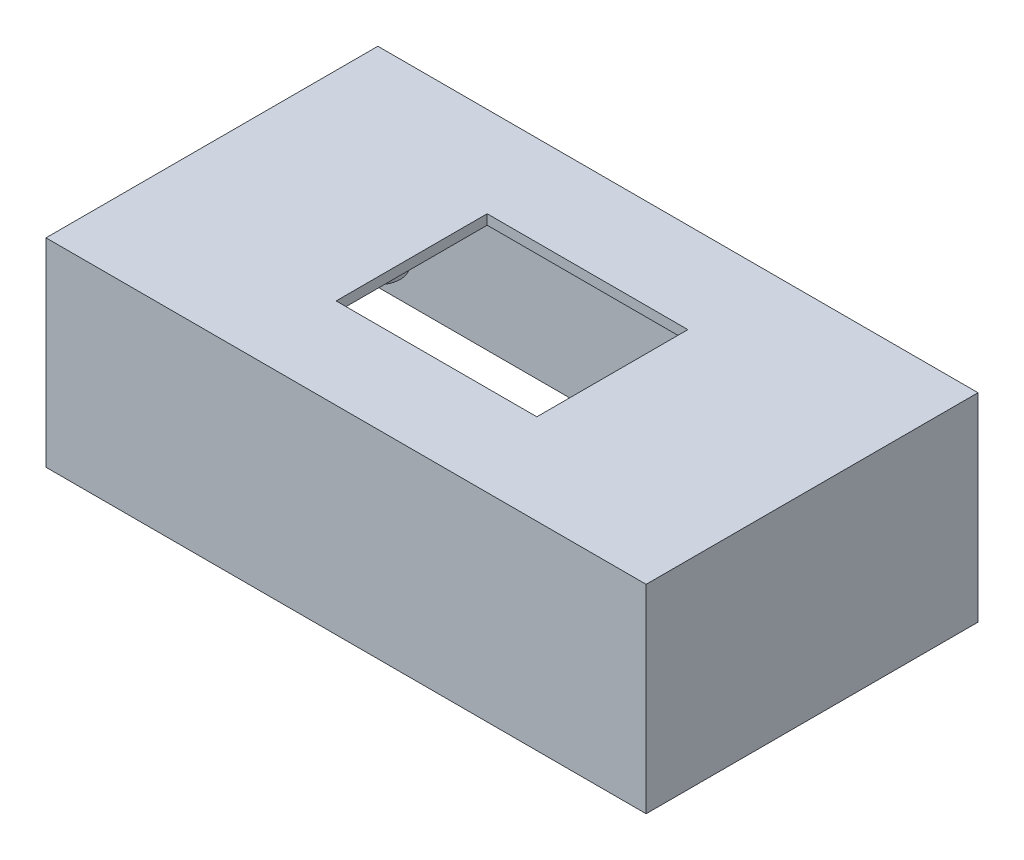
SolidWorks part; units mm, degrees
ref_plane "Front Plane" through (0, 0, 0) normal (0, 0, 1) x (1, 0, 0)
ref_plane "Top Plane" through (0, 0, 0) normal (0, 1, 0) x (1, 0, 0)
ref_plane "Right Plane" through (0, 0, 0) normal (1, 0, 0) x (0, 0, -1)
sketch "Sketch1" plane through (0, 0, 0) normal (0, 1, 0) x (1, 0, 0)
  line L0 (-29.2, 15.7) -> (29.2, 15.7)
  line L1 (-29, -15.5) -> (29, -15.5) construction
  line L2 (-29, -15.5) -> (-29, 15.5) construction
  line L3 (-29, 15.5) -> (29, 15.5) construction
  line L4 (29, -15.5) -> (29, 15.5) construction
  line L5 (-29, -15.5) -> (29, 15.5) construction
  line L6 (-29, 15.5) -> (29, -15.5) construction
  line L7 (29.2, -15.7) -> (29.2, 15.7)
  line L8 (-29.2, -15.7) -> (29.2, -15.7)
  line L9 (-29.2, -15.7) -> (-29.2, 15.7)
  line L10 (-30.2, -16.7) -> (-30.2, 16.7)
  line L11 (-30.2, 16.7) -> (30.2, 16.7)
  line L12 (30.2, -16.7) -> (30.2, 16.7)
  line L13 (-30.2, -16.7) -> (30.2, -16.7)
  point P0 (0, 0)
  dimension "D1" = 58
  dimension "D2" = 31
  dimension "D3" = 0.2
  dimension "D4" = 1
extrude "Boss-Extrude1" add sketch "Sketch1" along normal blind 19
sketch "Sketch2" plane through (0, 19, 0) normal (0, 1, 0) x (1, 0, 0)
  line L0 (-30.2, 16.7) -> (-30.2, -16.7) construction
  line L1 (-30.2, -16.7) -> (30.2, -16.7) construction
  line L2 (30.2, -16.7) -> (30.2, 16.7) construction
  line L3 (30.2, 16.7) -> (-30.2, 16.7) construction
  line L4 (-30.2, 16.7) -> (-30.2, -16.7)
  line L5 (-30.2, -16.7) -> (30.2, -16.7)
  line L6 (30.2, -16.7) -> (30.2, 16.7)
  line L7 (30.2, 16.7) -> (-30.2, 16.7)
  line L8 (0, 0) -> (30.2, 0) construction
  line L9 (-10.1, -7.6) -> (10.1, -7.6)
  line L10 (-10.1, -7.6) -> (-10.1, 7.6)
  line L11 (-10.1, 7.6) -> (10.1, 7.6)
  line L12 (10.1, -7.6) -> (10.1, 7.6)
  line L13 (-10.1, -7.6) -> (10.1, 7.6) construction
  line L14 (-10.1, 7.6) -> (10.1, -7.6) construction
  point P2 (0, 0)
  dimension "D1" = 15.2
  dimension "D2" = 20.2
extrude "Boss-Extrude2" add sketch "Sketch2" along normal blind 1
sketch "Sketch3" plane through (0, 19, 0) normal (0, -1, 0) x (1, 0, 0)
  line L0 (0, 16.7) -> (0, -16.7) construction
  line L1 (-30.2, 16.7) -> (30.2, 16.7) construction
  line L2 (30.2, -16.7) -> (-30.2, -16.7) construction
  line L4 (30.2, 16.7) -> (30.2, -16.7) construction
  line L5 (30.2, 0) -> (-30.2, 0) construction
  line L6 (-30.2, -16.7) -> (-30.2, 16.7) construction
  line L8 (-29.2, 15.7) -> (29.2, 15.7) construction
  line L10 (-29.2, 15.7) -> (-26, 15.7)
  line L11 (29.2, 12.5) -> (29.2, 15.7)
  line L12 (-26, 15.5923) -> (-26, 15.7)
  line L13 (-29.0923, 12.5) -> (-29.2, 12.5)
  line L14 (29.0923, 12.5) -> (29.2, 12.5)
  line L15 (-29.2, 12.5) -> (-29.2, 15.7)
  line L16 (26, 15.5923) -> (26, 15.7)
  line L17 (29.2, 15.7) -> (26, 15.7)
  line L18 (29.2, -15.7) -> (26, -15.7)
  line L19 (26, -15.5923) -> (26, -15.7)
  line L20 (-29.2, -12.5) -> (-29.2, -15.7)
  line L21 (29.0923, -12.5) -> (29.2, -12.5)
  line L22 (-29.0923, -12.5) -> (-29.2, -12.5)
  line L23 (-26, -15.5923) -> (-26, -15.7)
  line L24 (29.2, -12.5) -> (29.2, -15.7)
  line L25 (-29.2, -15.7) -> (-26, -15.7)
  arc A0 (-28.1408, 11.8077) -> (-25.3077, 14.6408) centre (-26, 12.5) ccw
  circle A1 centre (-26, 12.5) radius 1.25
  circle A2 centre (26, 12.5) radius 1.25
  arc A3 (28.1408, 11.8077) -> (25.3077, 14.6408) centre (26, 12.5) cw
  arc A4 (28.1408, -11.8077) -> (25.3077, -14.6408) centre (26, -12.5) ccw
  circle A5 centre (26, -12.5) radius 1.25
  circle A6 centre (-26, -12.5) radius 1.25
  arc A7 (-28.1408, -11.8077) -> (-25.3077, -14.6408) centre (-26, -12.5) cw
  arc A8 (25.3077, -14.6408) -> (26, -15.5923) centre (25, -15.5923) cw
  arc A9 (28.1408, -11.8077) -> (29.0923, -12.5) centre (29.0923, -11.5) ccw
  arc A10 (28.1408, 11.8077) -> (29.0923, 12.5) centre (29.0923, 11.5) cw
  arc A11 (25.3077, 14.6408) -> (26, 15.5923) centre (25, 15.5923) ccw
  arc A12 (-29.0923, 12.5) -> (-28.1408, 11.8077) centre (-29.0923, 11.5) cw
  arc A13 (-26, 15.5923) -> (-25.3077, 14.6408) centre (-25, 15.5923) ccw
  arc A14 (-28.1408, -11.8077) -> (-29.0923, -12.5) centre (-29.0923, -11.5) cw
  arc A15 (-25.3077, -14.6408) -> (-26, -15.5923) centre (-25, -15.5923) ccw
  point P42 (26, -14.75)
  point P45 (28.25, -12.5)
  point P48 (28.25, 12.5)
  point P51 (26, 14.75)
  point P54 (-28.25, 12.5)
  point P57 (-26, 14.75)
  point P60 (-28.25, -12.5)
  point P63 (-26, -14.75)
  dimension "D3" = 4.5
  dimension "D4" = 2.5
  dimension "D6" = 1
  dimension "D7" = 1
  dimension "D1" = 52
  dimension "D2" = 25
  dimension "D5" = 3.2
extrude "Boss-Extrude3" add sketch "Sketch3" along normal offset from surface (14 mm away) 5 up to face at (0, 0, 0)
sketch "Sketch4" plane through (-30.2, 0, 0) normal (-1, 0, 0) x (0, 0, 1)
  line L0 (-4, 0) -> (-4, 4)
  line L1 (-16.7, 0) -> (16.7, 0) construction
  line L2 (-4, 4) -> (4, 4)
  line L3 (4, 4) -> (4, 0)
  line L4 (4, 0) -> (-4, 0)
  point P4 (0, 0)
  dimension "D1" = 8
  dimension "D2" = 4
extrude "Cut-Extrude1" cut sketch "Sketch4" against normal up to next
